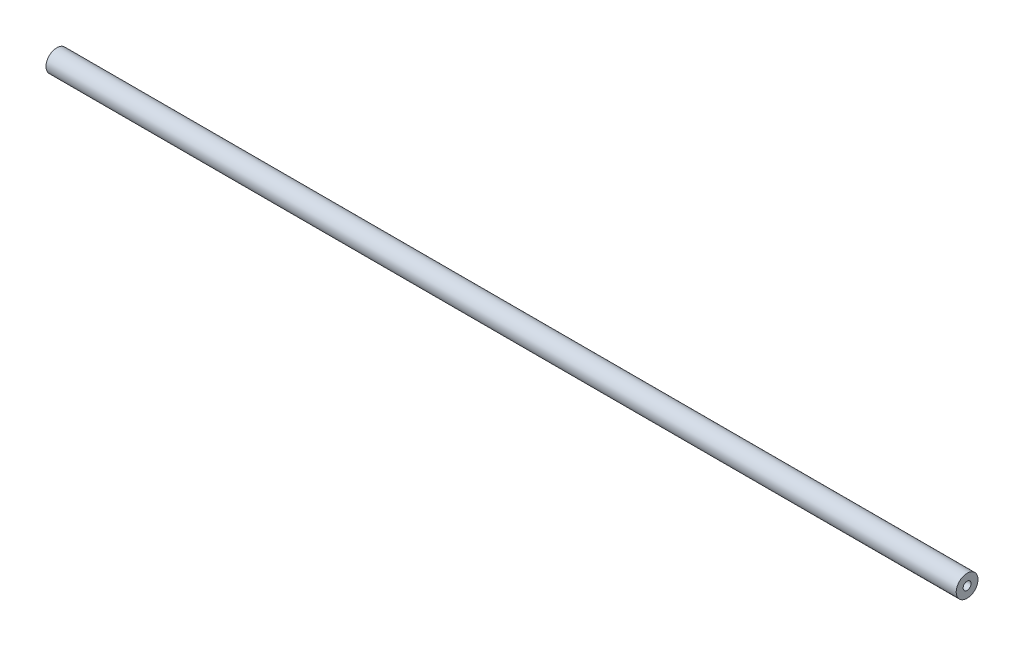
SolidWorks part; units mm, degrees
material "6061-T6 (SS)"
ref_plane "前视基准面" through (0, 0, 0) normal (0, 0, 1) x (1, 0, 0)
ref_plane "上视基准面" through (0, 0, 0) normal (0, 1, 0) x (1, 0, 0)
ref_plane "右视基准面" through (0, 0, 0) normal (1, 0, 0) x (0, 0, -1)
other "Configuration Table"
sketch "草图1" plane through (0, 0, 0) normal (1, 0, 0) x (0, 0, -1)
  circle A0 centre (0, 0) radius 1.65
  circle A1 centre (0, 0) radius 4.5
  dimension "D1" = 3.3
  dimension "D2" = 9
extrude "凸台-拉伸1" add sketch "草图1" along normal blind 376
